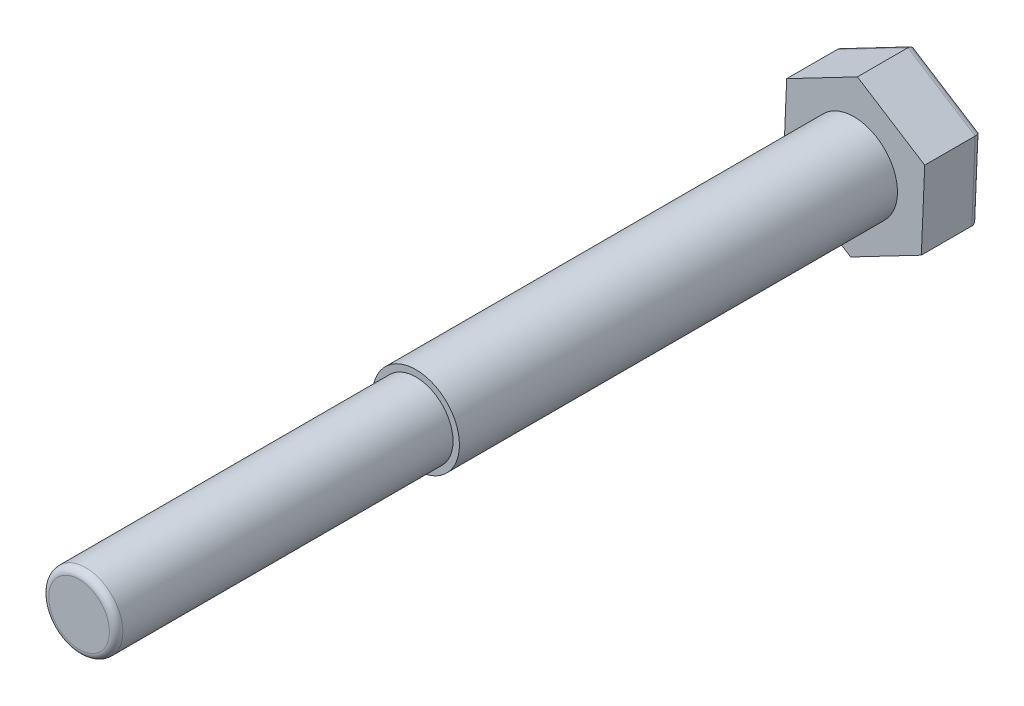
SolidWorks part; units mm, degrees
ref_plane "前视" through (0, 0, 0) normal (0, 0, 1) x (1, 0, 0)
ref_plane "上视" through (0, 0, 0) normal (0, 1, 0) x (1, 0, 0)
ref_plane "右视" through (0, 0, 0) normal (1, 0, 0) x (0, 0, -1)
sketch "草图1" plane through (0, 0, 0) normal (0, 0, 1) x (1, 0, 0)
  line L1 (20.9842, 10.9543) -> (1.0054, 23.65)
  line L2 (1.0054, 23.65) -> (-19.9788, 12.6957)
  line L3 (-19.9788, 12.6957) -> (-20.9842, -10.9543)
  line L4 (-20.9842, -10.9543) -> (-1.0054, -23.65)
  line L5 (-1.0054, -23.65) -> (19.9788, -12.6957)
  line L6 (19.9788, -12.6957) -> (20.9842, 10.9543)
  circle A0 centre (0, 0) radius 20.5 construction
  dimension "D1" = 47.3
  dimension "D2" = 41
extrude "基体-拉伸" add sketch "草图1" along normal blind 17
sketch "草图2" plane through (0, 0, 17) normal (0, 0, 1) x (1, 0, 0)
  circle A0 centre (0, 0) radius 12.9
  dimension "D1" = 25.8
extrude "凸台-拉伸1" add sketch "草图2" along normal blind 130
fillet "圆角3" radius 2 6 edges at (9.4867, -18.1729, 0) (-10.9948, -17.3021, 0) (-20.4815, 0.8707, 0) (-9.4867, 18.1729, 0) (10.9948, 17.3021, 0) (20.4815, -0.8707, 0)
sketch "草图3" plane through (0, 0, 147) normal (0, 0, 1) x (1, 0, 0)
  circle A0 centre (0, 0) radius 11
  dimension "D1" = 22
extrude "凸台-拉伸2" add sketch "草图3" along normal blind 100
fillet "圆角4" radius 2 1 edges at (11, 0, 247)
